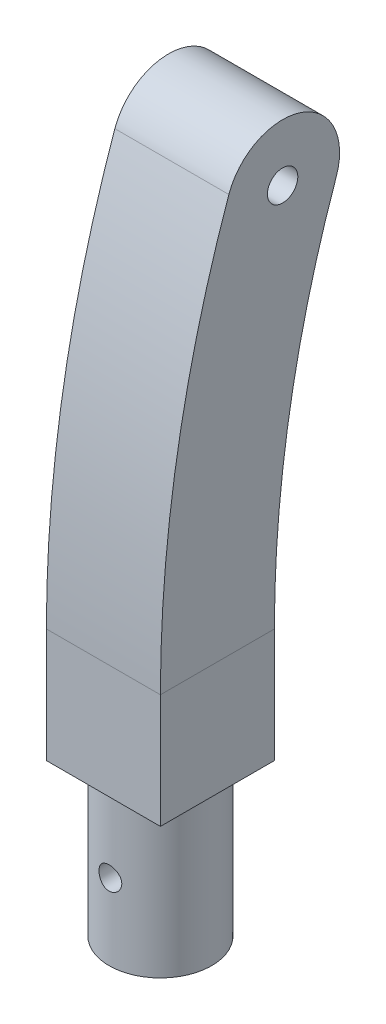
SolidWorks part; units mm, degrees
ref_plane "Front Plane" through (0, 0, 0) normal (0, 0, 1) x (1, 0, 0)
ref_plane "Top Plane" through (0, 0, 0) normal (0, 1, 0) x (1, 0, 0)
ref_plane "Right Plane" through (0, 0, 0) normal (1, 0, 0) x (0, 0, -1)
sketch "Sketch1" plane through (0, 0, 0) normal (1, 0, 0) x (0, 0, -1)
  line L0 (0, 0) -> (0, 30)
  line L1 (0, 30) -> (300, 30) construction
  line L2 (300, 30) -> (300, 130) construction
  line L3 (300, 130) -> (17.1573, 130) construction
  arc A0 (17.1573, 130) -> (0, 30) centre (300, 30) ccw
  dimension "D2" = 300
  dimension "D1" = 30
  dimension "D3" = 100
sketch "Sketch2" plane through (0, 0, 0) normal (0, 1, 0) x (1, 0, 0)
  line L1 (-15, -15) -> (15, -15)
  line L2 (-15, -15) -> (-15, 15)
  line L3 (-15, 15) -> (15, 15)
  line L4 (15, -15) -> (15, 15)
  line L5 (-15, -15) -> (15, 15) construction
  line L6 (-15, 15) -> (15, -15) construction
  point P0 (0, 0)
  dimension "D1" = 30
  dimension "D2" = 30
sweep "Sweep1" add profiles "Sketch2" path "Sketch1"
sketch "Sketch3" plane through (0, 0, 0) normal (0, -1, 0) x (1, 0, 0)
  circle A0 centre (0, 0) radius 13.5
  dimension "D1" = 27
extrude "Boss-Extrude1" add sketch "Sketch3" along normal blind 40
sketch "Sketch4" plane through (15, 0, 0) normal (1, 0, 0) x (0, 0, -1)
  line L0 (3.0152, 135) -> (31.2994, 125) construction
  line L1 (3.0152, 135) -> (31.2994, 125)
  arc A0 (31.2994, 125) -> (3.0152, 135) centre (17.1573, 130) ccw
extrude "Boss-Extrude2" add sketch "Sketch4" against normal up to surface (30 mm away) up to face at (-15, 80.3653, -6.4495)
sketch "Sketch5" plane through (15, 0, 0) normal (1, 0, 0) x (0, 0, -1)
  circle A0 centre (17.1573, 130) radius 4
  dimension "D1" = 8
extrude "Cut-Extrude1" cut sketch "Sketch5" against normal up to next
sketch "Sketch6" plane through (0, 0, 15) normal (0, 0, 1) x (1, 0, 0)
  circle A0 centre (0, -20) radius 3
  dimension "D1" = 6
extrude "Cut-Extrude2" cut sketch "Sketch6" against normal up to next
